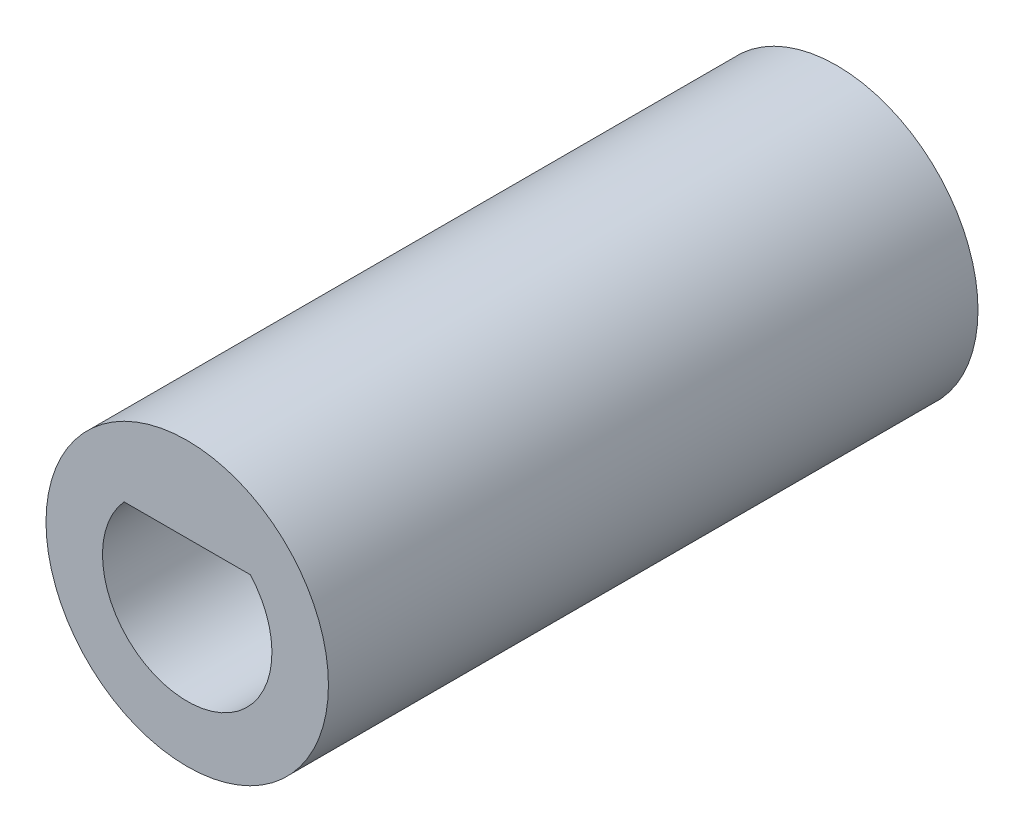
SolidWorks part; units mm, degrees
ref_plane "前视基准面" through (0, 0, 0) normal (0, 0, 1) x (1, 0, 0)
ref_plane "上视基准面" through (0, 0, 0) normal (0, 1, 0) x (1, 0, 0)
ref_plane "右视基准面" through (0, 0, 0) normal (1, 0, 0) x (0, 0, -1)
other "Configuration Table"
sketch "草图1" plane through (0, 0, 0) normal (0, 0, 1) x (1, 0, 0)
  circle A0 centre (0, 0) radius 5
  dimension "D1" = 10
extrude "凸台-拉伸1" add sketch "草图1" along normal blind 23
sketch "草图2" plane through (0, 0, 23) normal (0, 0, 1) x (1, 0, 0)
  line L0 (-7.7281, 2) -> (49992.2719, 2) construction
  line L1 (-2.2361, 2) -> (2.2361, 2)
  arc A0 (-2.2361, 2) -> (2.2361, 2) centre (0, 0) ccw
  point P7 (0, 0)
  point P8 (0, 0)
  dimension "D1" = 6
  dimension "D2" = 2
extrude "切除-拉伸1" cut sketch "草图2" against normal blind 10
sketch "草图3" plane through (0, 0, 0) normal (0, 0, -1) x (-1, 0, 0)
  circle A0 centre (0, 0) radius 4
  dimension "D1" = 8
extrude "切除-拉伸2" cut sketch "草图3" against normal blind 13
